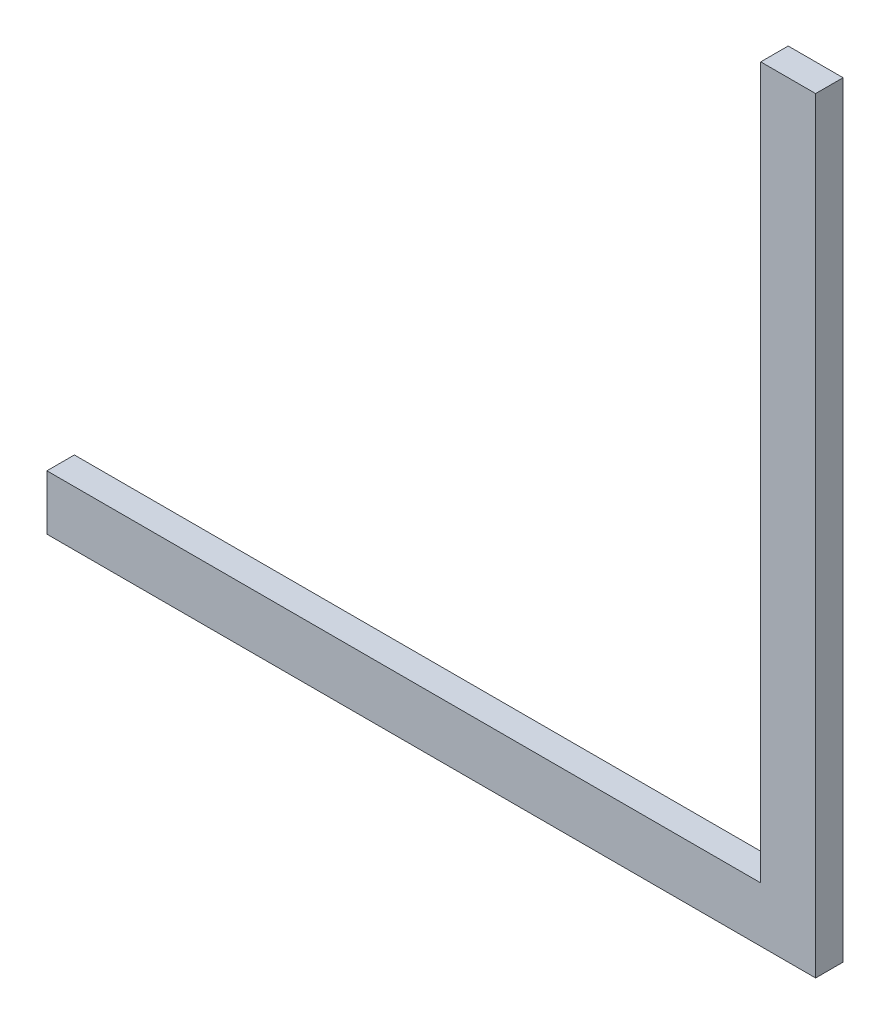
SolidWorks part; units mm, degrees
ref_plane "Ön Düzlem" through (0, 0, 0) normal (1, 0, 0) x (0, 1, 0)
ref_plane "Üst Düzlem" through (0, 0, 0) normal (0, 0, 1) x (0, 1, 0)
ref_plane "Sağ Düzlem" through (0, 0, 0) normal (0, 1, 0) x (-1, 0, 0)
sketch "Çizim1" plane through (0, 0, 0) normal (0, 0, 1) x (0, 1, 0)
  line L0 (0, 0) -> (0, 26)
  line L2 (2, 26) -> (2, 2)
  line L3 (2, 2) -> (25.9, 2)
  line L5 (25.9, 0) -> (0, 0)
  line L6 (0, 26) -> (0, 28)
  line L7 (0, 28) -> (2, 28)
  line L8 (2, 28) -> (2, 26)
  line L9 (25.9, 2) -> (27.9, 2)
  line L10 (27.9, 2) -> (27.9, 0)
  line L11 (27.9, 0) -> (25.9, 0)
  dimension "D1" = 2
  dimension "D2" = 25.9
  dimension "D3" = 26
extrude "Yükseklik-Ekstrüzyon1" add sketch "Çizim1" along normal blind 1
